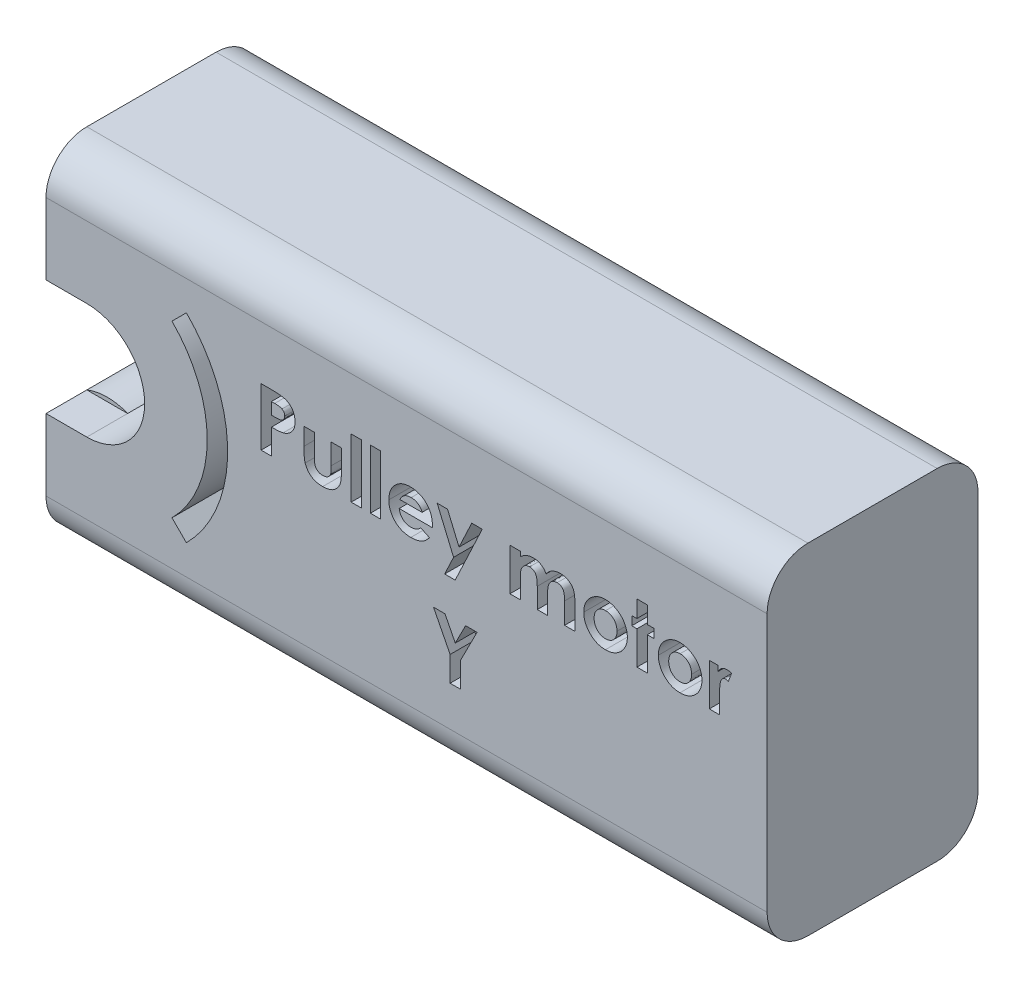
SolidWorks part; units mm, degrees
ref_plane "Front Plane" through (0, 0, 0) normal (0, 0, 1) x (1, 0, 0)
ref_plane "Top Plane" through (0, 0, 0) normal (0, 1, 0) x (1, 0, 0)
ref_plane "Right Plane" through (0, 0, 0) normal (1, 0, 0) x (0, 0, -1)
sketch "Croquis1" plane through (0, 0, 0) normal (0, 0, 1) x (1, 0, 0)
  line L0 (0, 0) -> (0, 25)
  line L1 (0, 25) -> (-50, 25)
  line L2 (-50, 25) -> (-50, 16.75)
  line L3 (0, 0) -> (-50, 0)
  line L4 (-50, 0) -> (-50, 8.25)
  line L5 (0, 12.5) -> (-50, 12.5) construction
  line L6 (-50, 16.75) -> (-50, 8.25) construction
  arc A0 (-50, 16.75) -> (-50, 8.25) centre (-50, 12.5) cw
  dimension "D2" = 4.25
  dimension "D1" = 50
  dimension "D3" = 25
extrude "Saliente-Extruir1" add sketch "Croquis1" along normal blind 15.5
sketch "Croquis2" plane through (0, 0, 0) normal (0, 0, -1) x (-1, 0, 0)
  line L0 (50, 7.25) -> (50, 5.25)
  line L1 (50, 17.75) -> (50, 19.75)
  line L2 (50, 8.25) -> (50, 0) construction
  line L4 (50, 25) -> (50, 16.75) construction
  arc A1 (50, 19.75) -> (50, 5.25) centre (50, 12.5) ccw
  arc A2 (50, 17.75) -> (50, 7.25) centre (50, 12.5) ccw
  arc A3 (50, 16.75) -> (50, 8.25) centre (50, 12.5) ccw construction
  dimension "D2" = 5.25
  dimension "D1" = 2
extrude "Saliente-Extruir2" [suppressed] add sketch "Croquis2" along normal blind 4
sketch "Croquis3" plane through (0, 0, 15.5) normal (0, 0, 1) x (1, 0, 0)
  line L0 (-50, 12.5) -> (-42.6814, 19.8186)
  line L1 (-50, 12.5) -> (-42.6814, 5.1814)
  line L2 (-50, 8.25) -> (-50, 0) construction
  circle A0 centre (-50, 12.5) radius 10.35
  circle A1 centre (-50, 12.5) radius 8.85
  dimension "D1" = 17.7
  dimension "D2" = 20.7
  dimension "D3" = 90
  dimension "D4" = 45
extrude "Cortar-Extruir1" cut sketch "Croquis3" against normal blind 5 contours A1 L1 A0 L0
sketch "Croquis4" plane through (0, 0, 15.5) normal (0, 0, 1) x (1, 0, 0)
  text T0 "<b>Pulley motor </b>\r\n<b>        Y</b>" font "Century Gothic" height in points 16
extrude "Cortar-Extruir2" cut sketch "Croquis4" against normal blind 2
sketch "Croquis6" plane through (-50, 0, 0) normal (-1, 0, 0) x (0, 0, 1)
  line L8 (0, 25) -> (0, 16.75)
  line L13 (0, 16.75) -> (15.5, 16.75)
  line L14 (15.5, 16.75) -> (15.5, 25)
  line L15 (15.5, 25) -> (0, 25)
  line L16 (0, 25) -> (0, 16.75)
  line L21 (0, 16.75) -> (15.5, 16.75)
  line L22 (15.5, 16.75) -> (15.5, 25)
  line L23 (15.5, 25) -> (0, 25)
  line L24 (0, 8.25) -> (0, 0)
  line L29 (0, 0) -> (15.5, 0)
  line L30 (15.5, 0) -> (15.5, 8.25)
  line L31 (15.5, 8.25) -> (0, 8.25)
  line L32 (0, 8.25) -> (0, 0)
  line L37 (0, 0) -> (15.5, 0)
  line L38 (15.5, 0) -> (15.5, 8.25)
  line L39 (15.5, 8.25) -> (0, 8.25)
  dimension "D1" = 0
  dimension "D2" = 0
extrude "Saliente-Extruir3" add sketch "Croquis6" along normal blind 3
fillet "Redondeo1" radius 3 4 edges at (-26.5, 25, 15.5) (-26.5, 0, 15.5) (-26.5, 25, 0) (-26.5, 0, 0)
sketch "Croquis7" plane through (0, 0, 15.5) normal (0, 0, 1) x (1, 0, 0)
  line L0 (-53, 16.75) -> (-50, 16.75)
  line L1 (-53, 8.25) -> (-50, 8.25)
  arc A0 (-50, 16.75) -> (-53, 16.75) centre (-51.5, 20.4581) cw
  arc A1 (-53, 8.25) -> (-50, 8.25) centre (-51.5, 4.5419) cw
  dimension "D1" = 4
extrude "Saliente-Extruir4" add sketch "Croquis7" against normal offset from surface (9.5 mm away) 3 from offset 3 up to face at (-38.4688, 12.5, 0)
